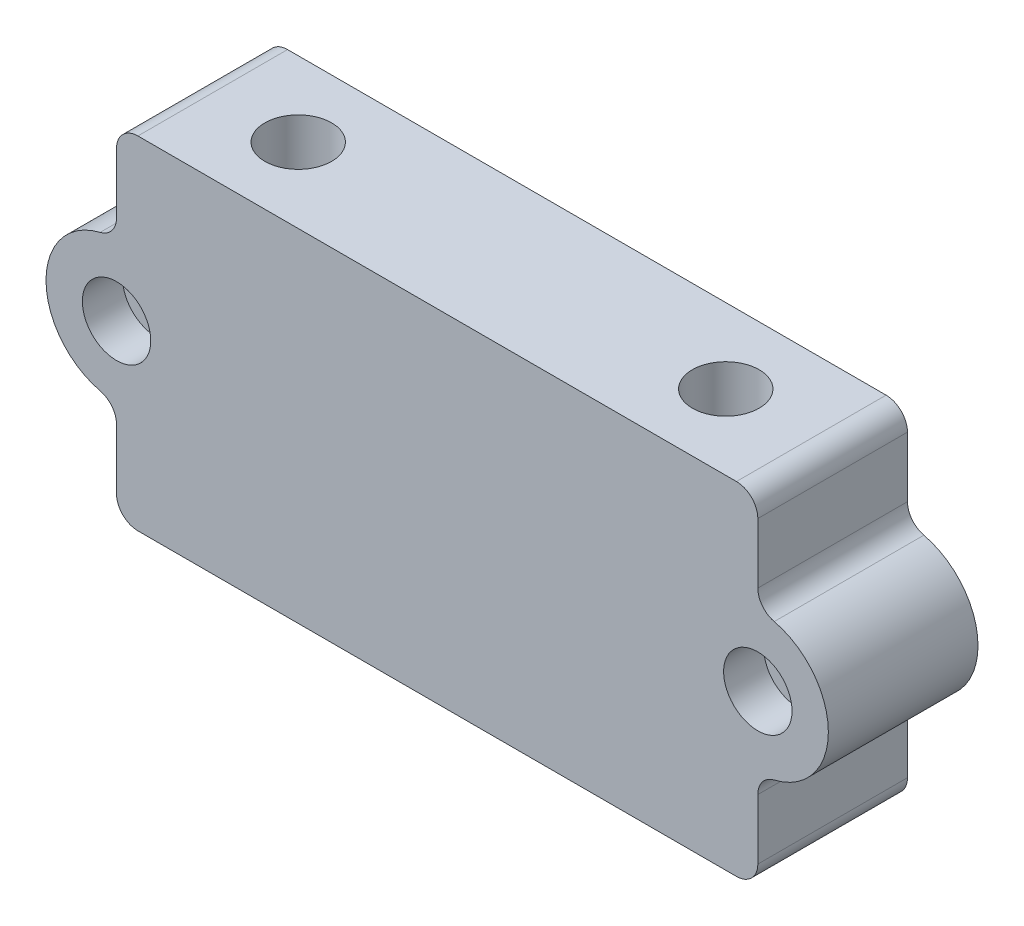
SolidWorks part; units mm, degrees
material "6061-T6 (SS)"
ref_plane "X-Y Datum" through (0, 0, 0) normal (0, 0, 1) x (1, 0, 0)
ref_plane "X-Z Datum" through (0, 0, 0) normal (0, 1, 0) x (1, 0, 0)
ref_plane "Y-Z Datum" through (0, 0, 0) normal (1, 0, 0) x (0, 0, -1)
other "Graphic1"
other "Graphic (Closed) -1"
other "Graphic2"
other "Graphic (Closed) -2"
other "Graphic3"
other "Graphic (Closed) -3"
sketch "Sketch1" plane through (0, 0, 0) normal (0, 0, 1) x (1, 0, 0)
  line L5 (-93.6625, 0) -> (0, 0) construction
  line L7 (-93.6625, -20.32) -> (-93.6625, 20.32)
  line L17 (-93.6625, -20.32) -> (0, -20.32)
  line L30 (-93.6625, 20.32) -> (0, 20.32)
  line L31 (0, 20.32) -> (0, -20.32)
  circle A4 centre (-84.9313, 0) radius 2.4892
  circle A7 centre (-8.7312, 0) radius 2.4892
  point P1 (-93.6625, 0)
  point P4 (-73.2082, 0)
  point P11 (-14.3557, 0)
  dimension "D2" = 93.6625
  dimension "D3" = 8.7312
  dimension "D1" = 8.7312
  dimension "D4" = 40.64
extrude "Boss-Extrude1" add sketch "Sketch1" against normal blind 17.78
sketch "Sketch3" plane through (0, 0, 0) normal (0, 0, 1) x (1, 0, 0)
  circle A2 centre (-84.9313, 0) radius 4.064
  circle A3 centre (-84.9313, 0) radius 2.4892 construction
  circle A4 centre (-8.7312, 0) radius 4.064
  point P3 (-8.7312, 0)
  dimension "D1" = 8.128
sketch "Sketch6" plane through (0, 20.32, 0) normal (0, 1, 0) x (1, 0, 0)
  line L0 (0, 17.78) -> (-93.6625, 17.78) construction
  line L1 (-72.2313, 8.89) -> (-21.4312, 8.89) construction
  circle A0 centre (-72.2313, 8.89) radius 3.9687
  circle A1 centre (-21.4312, 8.89) radius 3.9687
  point P4 (-46.8312, 17.78)
  point P5 (-46.8312, 8.89)
  dimension "D1" = 7.9375
  dimension "D2" = 8.89
  dimension "D3" = 50.8
extrude "Cut-Extrude4" cut sketch "Sketch6" against normal through all
sketch "Sketch5" plane through (0, 0, 0) normal (0, 0, 1) x (1, 0, 0)
  line L7 (-46.8312, 20.32) -> (-46.8313, -20.32) construction
  line L8 (0, 20.32) -> (-93.6625, 20.32) construction
  line L18 (-93.6625, -20.32) -> (0, -20.32) construction
  line B0 (-93.6625, -20.32) -> (-93.6625, 20.32)
  line B1 (-84.9312, -20.32) -> (-93.6625, -20.32)
  line B2 (-84.9313, -10.6225) -> (-84.9312, -20.32)
  line B3 (-84.9313, 10.6225) -> (-84.9312, 20.32)
  line B4 (-93.6625, 20.32) -> (-84.9312, 20.32)
  arc B5 (-84.9313, -10.6225) -> (-86.8806, -8.1522) centre (-87.4713, -10.6225) ccw
  arc B6 (-86.8806, 8.1522) -> (-86.8806, -8.1522) centre (-84.9313, 0) ccw
  arc B7 (-84.9313, 10.6225) -> (-86.8806, 8.1522) centre (-87.4713, 10.6225) cw
  line B8 (0, -20.32) -> (0, 20.32)
  line B9 (-8.7313, -20.32) -> (0, -20.32)
  line B10 (-8.7313, -10.6225) -> (-8.7313, -20.32)
  line B11 (-8.7312, 10.6225) -> (-8.7312, 20.32)
  line B12 (0, 20.32) -> (-8.7312, 20.32)
  arc B13 (-8.7313, -10.6225) -> (-6.7819, -8.1522) centre (-6.1912, -10.6225) cw
  arc B14 (-6.7819, 8.1522) -> (-6.7819, -8.1522) centre (-8.7312, 0) cw
  arc B15 (-8.7312, 10.6225) -> (-6.7819, 8.1522) centre (-6.1912, 10.6225) ccw
sketch_block_instance "Block1-1"
sketch_block "Block1"
sketch_block_instance "Block1-2"
extrude "Cut-Extrude3" cut sketch "Sketch5" against normal up to surface (17.78 mm away) up to face at (-6.242, 0, -17.78)
fillet "Fillet1" radius 2.54 4 edges at (-84.9312, -20.32, -8.89) (-8.7313, -20.32, -8.89) (-8.7312, 20.32, -8.89) (-84.9312, 20.32, -8.89)
extrude "Cut-Extrude5" cut sketch "Sketch3" against normal blind 4.7752
